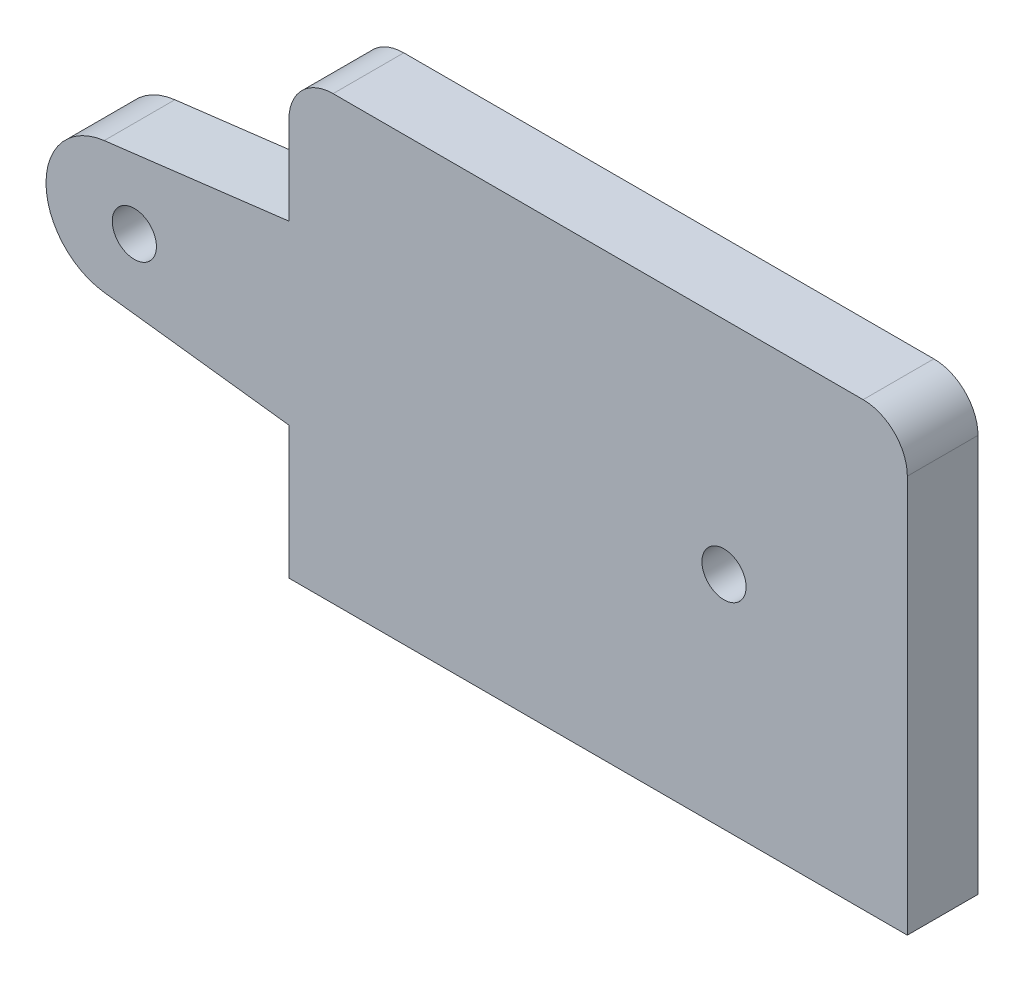
SolidWorks part; units mm, degrees
ref_plane "Front Plane" through (0, 0, 0) normal (0, 0, 1) x (1, 0, 0)
ref_plane "Top Plane" through (0, 0, 0) normal (0, 1, 0) x (1, 0, 0)
ref_plane "Right Plane" through (0, 0, 0) normal (1, 0, 0) x (0, 0, -1)
sketch "Sketch1" plane through (0, 0, 0) normal (0, 0, 1) x (1, 0, 0)
  line L0 (-35, 10) -> (-55.9098, 7.4446)
  line L1 (-30, 25) -> (30, 25)
  line L2 (-35, 20) -> (-35, -25)
  line L3 (-35, -25) -> (35, -25)
  line L4 (35, 20) -> (35, -25)
  line L5 (-35, 25) -> (35, -25) construction
  line L6 (-35, -25) -> (35, 25) construction
  line L7 (-35, -10) -> (-55.9098, -7.4446)
  arc A0 (-30, 25) -> (-35, 20) centre (-30, 20) ccw
  arc A1 (30, 25) -> (35, 20) centre (30, 20) cw
  circle A2 centre (-55, 0) radius 7.5
  circle A4 centre (14.25, 0) radius 2.5
  circle A6 centre (-52.5, 0) radius 2.5 construction
  circle A7 centre (-52.5, 0) radius 2.5
  point P0 (0, 0)
  dimension "D3" = 5
  dimension "D4" = 15
  dimension "D11" = 5
  dimension "D1" = 70
  dimension "D2" = 50
  dimension "D7" = 15
  dimension "D8" = 15
  dimension "D9" = 25
  dimension "D10" = 20.75
extrude "Boss-Extrude3" add sketch "Sketch1" along normal blind 8
